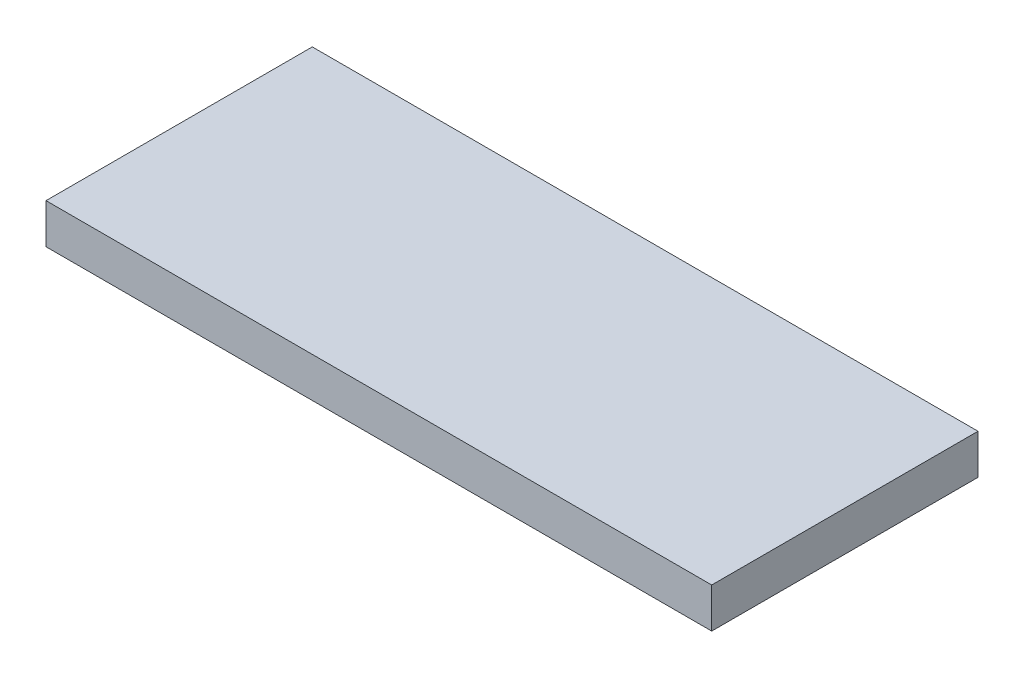
SolidWorks part; units mm, degrees
ref_plane "Front Plane" through (0, 0, 0) normal (0, 0, 1) x (1, 0, 0)
ref_plane "Top Plane" through (0, 0, 0) normal (0, 1, 0) x (1, 0, 0)
ref_plane "Right Plane" through (0, 0, 0) normal (1, 0, 0) x (0, 0, -1)
other "Configuration Table"
sketch "草图1" plane through (0, 0, 0) normal (0, 1, 0) x (1, 0, 0)
  line L0 (0, -10) -> (0, 10) construction
  line L1 (-25, -10) -> (25, -10)
  line L2 (-25, -10) -> (-25, 10)
  line L3 (-25, 10) -> (25, 10)
  line L4 (25, -10) -> (25, 10)
  line L5 (-25, -10) -> (25, 10) construction
  line L6 (-25, 10) -> (25, -10) construction
  point P0 (0, 0)
  point P8 (0, -10)
  dimension "D1" = 50
  dimension "D2" = 20
extrude "凸台-拉伸1" add sketch "草图1" along normal blind 3
sketch "草图2" plane through (0, 3, 0) normal (0, 1, 0) x (1, 0, 0)
  line L0 (0, -10) -> (0, 10) construction
  line L3 (-25, -10) -> (25, -10) construction
  line L4 (-25, 10) -> (-25, -10) construction
  line L5 (17.261, -10) -> (25, -10)
  line L9 (25, -10) -> (25, 10)
  line L10 (25, 10) -> (-25, 10)
  line L11 (-25, 10) -> (-25, -10)
  line L12 (-25, -10) -> (25, -10)
  line L13 (25, -10) -> (25, -2.261)
  line L15 (-25, -2.261) -> (-25, -10)
  line L16 (-25, -10) -> (-17.261, -10)
  arc A0 (-17.261, -10) -> (-25, -2.261) centre (-25, -10) ccw
  arc A1 (17.261, -10) -> (25, -2.261) centre (25, -10) cw
  dimension "D1" = 0
